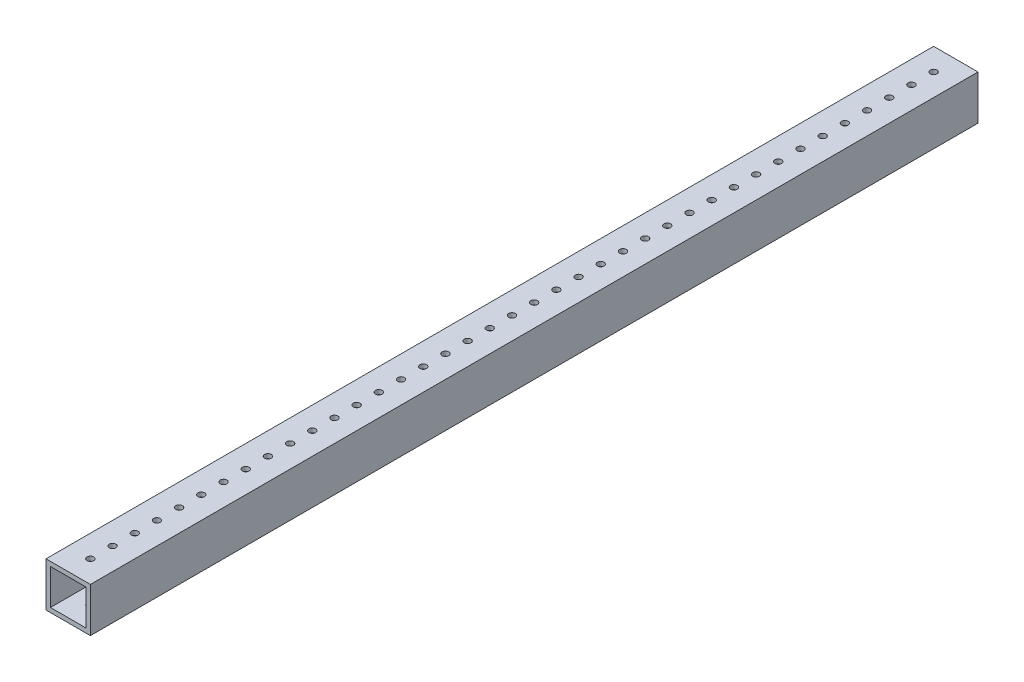
SolidWorks part; units mm, degrees
ref_plane "前视基准面" through (0, 0, 0) normal (0, 0, 1) x (1, 0, 0)
ref_plane "上视基准面" through (0, 0, 0) normal (0, 1, 0) x (1, 0, 0)
ref_plane "右视基准面" through (0, 0, 0) normal (1, 0, 0) x (0, 0, -1)
sketch "草图1" plane through (0, 0, 0) normal (0, 0, 1) x (1, 0, 0)
  line L1 (0, 20) -> (20, 20)
  line L2 (0, 20) -> (0, 0)
  line L3 (0, 0) -> (20, 0)
  line L4 (20, 20) -> (20, 0)
  line L5 (2, 18) -> (18, 18)
  line L6 (2, 18) -> (2, 2)
  line L7 (2, 2) -> (18, 2)
  line L8 (18, 18) -> (18, 2)
  dimension "D1" = 20
  dimension "D2" = 20
  dimension "D3" = 2
  dimension "D4" = 2
  dimension "D5" = 2
  dimension "D6" = 2
extrude "凸台-拉伸1" add sketch "草图1" along normal blind 400
sketch "草图4" [suppressed] plane through (0, 0, 0) normal (-1, 0, 0) x (0, 0, 1)
  line L0 (0, 20) -> (753.1431, 20) construction
  line L1 (0, 40) -> (0, 0) construction
  line L2 (180, -10.7051) -> (180, 94.4528) construction
  line L3 (10, 10) -> (40, 10) construction
  line L4 (40, 10) -> (70, 10) construction
  line L5 (40, 30) -> (70, 30) construction
  line L6 (10, 30) -> (40, 30) construction
  line L7 (350, 30) -> (320, 30) construction
  line L8 (320, 30) -> (290, 30) construction
  line L9 (320, 10) -> (290, 10) construction
  line L10 (350, 10) -> (320, 10) construction
  line L11 (360, 0) -> (0, 0) construction
  line L13 (149.95, 17.05) -> (149.95, -19.8914)
  line L14 (149.95, -19.8914) -> (179.95, -19.8914)
  line L15 (179.95, 17.05) -> (179.95, -19.8914)
  line L20 (360, 40) -> (360, 0) construction
  line L21 (149.95, 20.05) -> (179.95, 20.05)
  line L22 (210.05, 20.05) -> (180.05, 20.05)
  line L23 (180.05, 17.05) -> (180.05, -19.8914)
  line L24 (210.05, -19.8914) -> (180.05, -19.8914)
  line L25 (210.05, 17.05) -> (210.05, -19.8914)
  circle A0 centre (10, 10) radius 1.5
  circle A1 centre (40, 10) radius 1.5
  circle A2 centre (70, 10) radius 1.5
  circle A3 centre (70, 30) radius 1.5
  circle A4 centre (40, 30) radius 1.5
  circle A5 centre (10, 30) radius 1.5
  circle A6 centre (350, 30) radius 1.5
  circle A7 centre (320, 30) radius 1.5
  circle A8 centre (290, 30) radius 1.5
  circle A9 centre (290, 10) radius 1.5
  circle A10 centre (320, 10) radius 1.5
  circle A11 centre (350, 10) radius 1.5
  arc A12 (149.95, 17.05) -> (149.95, 20.05) centre (149.95, 18.55) cw
  arc A13 (179.95, 20.05) -> (179.95, 17.05) centre (179.95, 18.55) cw
  arc A14 (180.05, 20.05) -> (180.05, 17.05) centre (180.05, 18.55) ccw
  arc A15 (210.05, 17.05) -> (210.05, 20.05) centre (210.05, 18.55) ccw
  dimension "D1" = 3
  dimension "D2" = 3
  dimension "D3" = 3
  dimension "D10" = 1.5
  dimension "D13" = 1.5
  dimension "D4" = 30
  dimension "D5" = 30
  dimension "D6" = 10
  dimension "D7" = 10
  dimension "D8" = 30
  dimension "D9" = 149.95
  dimension "D11" = 19.8914
  dimension "D12" = 20.05
  dimension "D14" = 17.05
sketch "草图9" plane through (0, 20, 0) normal (0, 1, 0) x (1, 0, 0)
  line L0 (10, 9.6997) -> (10, -367.1122) construction
  line L1 (0, -400) -> (0, 0) construction
  line L2 (20, -400) -> (20, 0) construction
  line L3 (20, -400) -> (0, -400) construction
  circle A0 centre (10, -390) radius 1.5
  circle A1 centre (10, -380) radius 1.5
  circle A2 centre (10, -370) radius 1.5
  circle A3 centre (10, -360) radius 1.5
  circle A4 centre (10, -350) radius 1.5
  circle A5 centre (10, -340) radius 1.5
  circle A6 centre (10, -330) radius 1.5
  circle A7 centre (10, -320) radius 1.5
  circle A8 centre (10, -310) radius 1.5
  circle A9 centre (10, -300) radius 1.5
  circle A10 centre (10, -290) radius 1.5
  circle A11 centre (10, -280) radius 1.5
  circle A12 centre (10, -270) radius 1.5
  circle A13 centre (10, -260) radius 1.5
  circle A14 centre (10, -250) radius 1.5
  circle A15 centre (10, -240) radius 1.5
  circle A16 centre (10, -230) radius 1.5
  circle A17 centre (10, -220) radius 1.5
  circle A18 centre (10, -210) radius 1.5
  circle A19 centre (10, -200) radius 1.5
  circle A20 centre (10, -190) radius 1.5
  circle A21 centre (10, -180) radius 1.5
  circle A22 centre (10, -170) radius 1.5
  circle A23 centre (10, -160) radius 1.5
  circle A24 centre (10, -150) radius 1.5
  circle A25 centre (10, -140) radius 1.5
  circle A26 centre (10, -130) radius 1.5
  circle A27 centre (10, -120) radius 1.5
  circle A28 centre (10, -110) radius 1.5
  circle A29 centre (10, -100) radius 1.5
  circle A30 centre (10, -90) radius 1.5
  circle A31 centre (10, -80) radius 1.5
  circle A32 centre (10, -70) radius 1.5
  circle A33 centre (10, -60) radius 1.5
  circle A34 centre (10, -50) radius 1.5
  circle A35 centre (10, -40) radius 1.5
  circle A36 centre (10, -30) radius 1.5
  circle A37 centre (10, -20) radius 1.5
  circle A38 centre (10, -10) radius 1.5
  dimension "D1" = 3
  dimension "D2" = 10
  dimension "D4" = 10
  dimension "D3" = 39
extrude "切除-拉伸6" cut sketch "草图9" against normal through all
